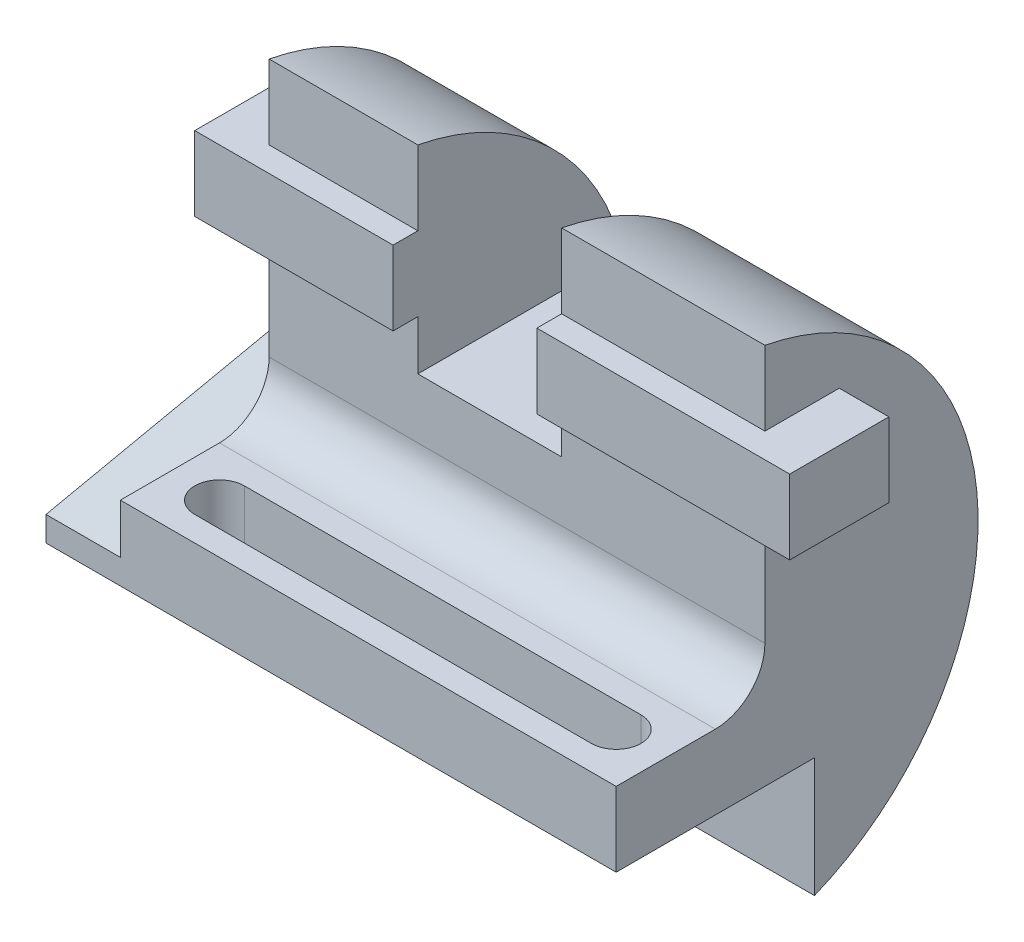
SolidWorks part; units mm, degrees
ref_plane "Front Plane" through (0, 0, 0) normal (0, 0, 1) x (1, 0, 0)
ref_plane "Top Plane" through (0, 0, 0) normal (0, 1, 0) x (1, 0, 0)
ref_plane "Right Plane" through (0, 0, 0) normal (1, 0, 0) x (0, 0, -1)
sketch "Sketch1" plane through (0, 0, 0) normal (1, 0, 0) x (0, 0, -1)
  line L5 (0, -10) -> (-20, -10)
  line L6 (-20, -10) -> (-20, -25)
  line L7 (-20, -25) -> (20, -25)
  line L9 (10, 0) -> (10, 52.0481)
  line L10 (20, -25) -> (20, -49.0816)
  arc A2 (0, -10) -> (10, 0) centre (0, 0) ccw
  arc A4 (10, 52.0481) -> (20, -49.0816) centre (0, 0) cw
  dimension "D4" = 10
  dimension "D5" = 53
  dimension "D1" = 40
  dimension "D2" = 15
  dimension "D3" = 20
extrude "Boss-Extrude1" add sketch "Sketch1" along normal blind 57.5 and the other way blind 42.5
sketch "Sketch2" plane through (0, 0, 0) normal (1, 0, 0) x (0, 0, -1)
  line L0 (10, 52.0481) -> (10, 0) construction
  line L1 (5, 37.0481) -> (25, 37.0481)
  line L2 (5, 37.0481) -> (5, 22.0481)
  line L3 (5, 22.0481) -> (25, 22.0481)
  line L4 (25, 37.0481) -> (25, 22.0481)
  dimension "D1" = 5
  dimension "D2" = 15
  dimension "D3" = 15
  dimension "D4" = 15
extrude "Boss-Extrude2" add sketch "Sketch2" along normal blind 67.5 and the other way blind 52.5
sketch "Sketch3" plane through (-42.5, 0, 0) normal (-1, 0, 0) x (0, 0, 1)
  line L0 (20, -25) -> (-20, -25)
  line L1 (-20, -25) -> (-20, -49.0816)
  line L2 (20, -25) -> (20, -20)
  line L3 (20, -10) -> (20, -25) construction
  line L4 (20, -20) -> (-52.8065, -4.5245)
  arc A0 (-10, 52.0481) -> (-20, -49.0816) centre (0, 0) ccw construction
  arc A1 (-52.8065, -4.5245) -> (-20, -49.0816) centre (0, 0) ccw
  dimension "D1" = 78
  dimension "D2" = 5
extrude "Boss-Extrude3" add sketch "Sketch3" along normal blind 15
sketch "Sketch4" plane through (0, -10, 0) normal (0, 1, 0) x (1, 0, 0)
  line L0 (-32.5, -5) -> (47.5, -5)
  line L1 (-32.5, -15) -> (47.5, -15)
  line L2 (-42.5, -20) -> (57.5, -20) construction
  line L3 (57.5, 0) -> (57.5, -20) construction
  arc A0 (-32.5, -5) -> (-32.5, -15) centre (-32.5, -10) ccw
  arc A1 (47.5, -5) -> (47.5, -15) centre (47.5, -10) cw
  dimension "D3" = 80
  dimension "D4" = 10
  dimension "D2" = 10
  dimension "D1" = 10
extrude "Cut-Extrude1" cut sketch "Sketch4" against normal through all
sketch "Sketch5" plane through (0, 0, 0) normal (0, 0, 1) x (1, 0, 0)
  line L0 (-42.5, 52.0481) -> (57.5, 52.0481) construction
  line L1 (-12.5, 52.0481) -> (16.5, 52.0481)
  line L2 (-12.5, 52.0481) -> (-12.5, 12.0481)
  line L3 (-12.5, 12.0481) -> (16.5, 12.0481)
  line L4 (16.5, 52.0481) -> (16.5, 12.0481)
  line L5 (-42.5, 52.0481) -> (-42.5, 37.0481) construction
  line L6 (-42.5, 22.0481) -> (57.5, 22.0481) construction
  dimension "D1" = 30
  dimension "D2" = 29
  dimension "D3" = 10
extrude "Cut-Extrude2" cut sketch "Sketch5" against normal through all both and the other way through all
